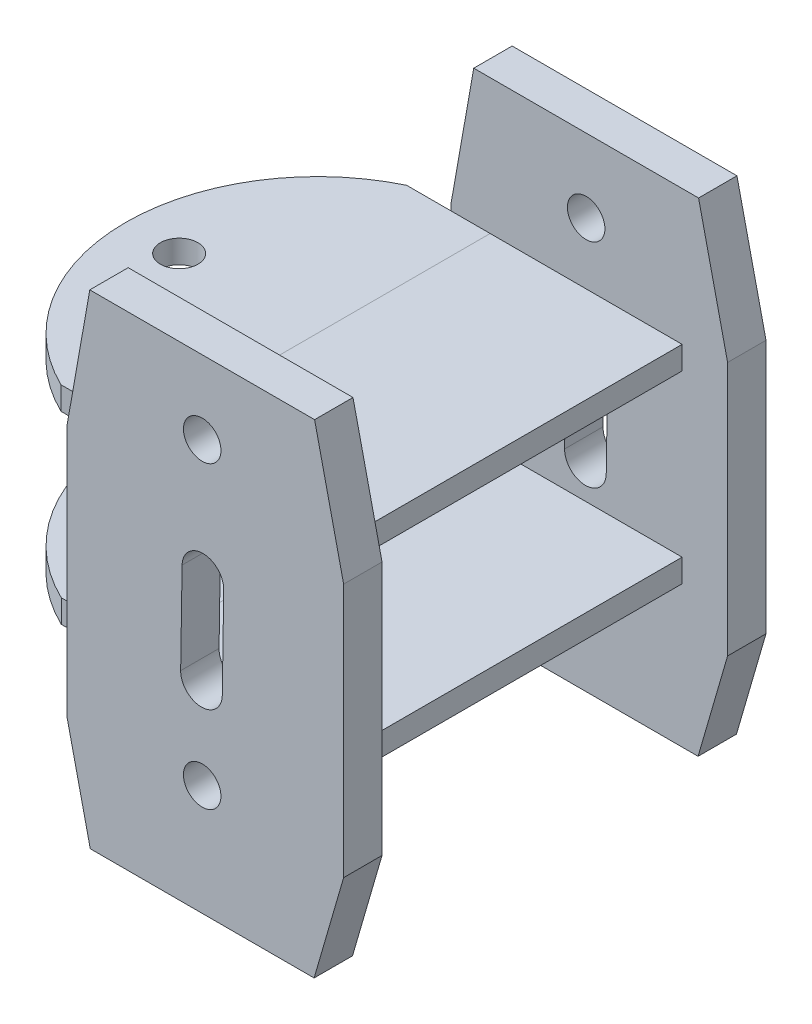
SolidWorks part; units mm, degrees
other "标注1"
sketch "草图13" plane through (-34.4412, -22.5305, 5) normal (-0.9848, -0.1608, 0.0653) x (-0.1462, 0.9714, 0.1873)
material "AISI 1020 钢，冷轧"
ref_plane "前视基准面" through (0, 0, 0) normal (0, 0, 1) x (1, 0, 0)
ref_plane "上视基准面" through (0, 0, 0) normal (0, 1, 0) x (1, 0, 0)
ref_plane "右视基准面" through (0, 0, 0) normal (1, 0, 0) x (0, 0, -1)
sketch "草图1" plane through (0, 0, 0) normal (0, 0, 1) x (1, 0, 0)
  line L0 (17.6966, 40.4695) -> (-11.579, 40.4695)
  line L1 (17.6339, -22.5305) -> (-11.5163, -22.5305)
  line L2 (17.6966, 40.4695) -> (21.478, 23.8119)
  line L3 (21.478, 23.8119) -> (21.478, -9.2898)
  line L4 (21.478, -9.2898) -> (17.6339, -22.5305)
  line L5 (-11.579, 40.4695) -> (-14.522, 23.8119)
  line L6 (-14.522, 23.8119) -> (-14.522, -9.2898)
  line L7 (-14.522, -9.2898) -> (-11.5163, -22.5305)
  line L8 (2.965, 3.401) -> (3.1525, 15.401) construction
  line L9 (-9.4412, 22.8926) -> (15.5588, 22.8926)
  line L12 (-9.4412, 22.8926) -> (-9.4412, 19.8926)
  line L17 (-9.4412, 19.8926) -> (15.5588, 19.8926)
  line L18 (15.5588, 22.8926) -> (15.5588, 19.8926)
  line L19 (-9.4412, 22.8926) -> (15.5588, 19.8926) construction
  line L20 (-9.4412, 19.8926) -> (15.5588, 22.8926) construction
  line L21 (-9.4412, -1.1074) -> (15.5588, -1.1074)
  line L22 (-9.4412, -1.1074) -> (-9.4412, -4.1074)
  line L23 (-9.4412, -4.1074) -> (15.5588, -4.1074)
  line L24 (15.5588, -1.1074) -> (15.5588, -4.1074)
  line L25 (-9.4412, -1.1074) -> (15.5588, -4.1074) construction
  line L26 (-9.4412, -4.1074) -> (15.5588, -1.1074) construction
  line L27 (0.255, 3.4434) -> (0.4425, 15.4434)
  line L28 (5.6751, 3.3587) -> (5.8626, 15.3587)
  circle A0 centre (3.0588, 30.8926) radius 2.44
  circle A1 centre (3.0588, -8.1074) radius 2.44
  arc A8 (0.255, 3.4434) -> (5.6751, 3.3587) centre (2.965, 3.401) ccw
  arc A9 (5.8626, 15.3587) -> (0.4425, 15.4434) centre (3.1525, 15.401) ccw
  point P1 (3.0588, 21.3926)
  point P17 (3.0588, -2.6074)
  point P24 (3.0588, 9.401)
  dimension "D1" = 63
  dimension "D2" = 36
  dimension "D6" = 25
  dimension "D7" = 25
  dimension "D8" = 3
  dimension "D9" = 3
  dimension "D10" = 12
  dimension "D11" = 4
  dimension "D12" = 8
extrude "凸台-拉伸1" add sketch "草图1" along normal blind 5
sketch "草图6" plane through (0, 0, 0) normal (0, 0, -1) x (-1, 0, 0)
  line L42 (9.4412, 22.8926) -> (-15.5588, 22.8926)
  line L43 (9.4412, 19.8926) -> (9.4412, 22.8926)
  line L44 (-15.5588, 19.8926) -> (9.4412, 19.8926)
  line L45 (-15.5588, 22.8926) -> (-15.5588, 19.8926)
  line L46 (9.4412, 22.8926) -> (-15.5588, 22.8926)
  line L47 (9.4412, 19.8926) -> (9.4412, 22.8926)
  line L48 (-15.5588, 19.8926) -> (9.4412, 19.8926)
  line L49 (-15.5588, 22.8926) -> (-15.5588, 19.8926)
  line L54 (-15.5588, -1.1074) -> (-15.5588, -4.1074)
  line L55 (-15.5588, -4.1074) -> (9.4412, -4.1074)
  line L56 (9.4412, -4.1074) -> (9.4412, -1.1074)
  line L57 (9.4412, -1.1074) -> (-15.5588, -1.1074)
  line L58 (-15.5588, -1.1074) -> (-15.5588, -4.1074)
  line L59 (-15.5588, -4.1074) -> (9.4412, -4.1074)
  line L60 (9.4412, -4.1074) -> (9.4412, -1.1074)
  line L61 (9.4412, -1.1074) -> (-15.5588, -1.1074)
  dimension "D1" = 0
  dimension "D2" = 0
extrude "凸台-拉伸5" add sketch "草图6" against normal blind 5 and the other way blind 22.5
mirror "镜向2" about plane through (0, 0, -22.5) normal (0, 0, -1) of bodies 106
sketch "草图7" plane through (-9.4412, 0, 0) normal (-1, 0, 0) x (0, 0, 1)
  line L14 (0, 19.8926) -> (0, 22.8926)
  line L15 (-45, 22.8926) -> (-45, 19.8926)
  line L16 (-45, 19.8926) -> (0, 19.8926)
  line L17 (0, 22.8926) -> (-45, 22.8926)
  line L18 (0, 19.8926) -> (0, 22.8926)
  line L19 (-45, 22.8926) -> (-45, 19.8926)
  line L20 (-45, 19.8926) -> (0, 19.8926)
  line L21 (0, 22.8926) -> (-45, 22.8926)
  dimension "D1" = 0
extrude "凸台-拉伸6" add sketch "草图7" along normal blind 25 separate body
sketch "草图8" plane through (0, 22.8926, 0) normal (0, 1, 0) x (1, 0, 0)
  line L4 (-9.4412, 0) -> (-9.4412, 45)
  line L5 (-9.4412, 45) -> (-34.4412, 45)
  line L6 (-34.4412, 45) -> (-34.4412, 0)
  line L7 (-34.4412, 0) -> (-9.4412, 0)
  line L9 (-9.4412, 45) -> (-34.4412, 45)
  line L10 (-34.4412, 45) -> (-34.4412, 0)
  line L11 (-34.4412, 0) -> (-9.4412, 0)
  line L12 (-9.4412, 0) -> (-9.4412, 45)
  arc A0 (-20.3254, 45) -> (-20.3254, 0) centre (-9.4281, 22.5) ccw
  line M8 (-34.4412, 45) -> (-34.4412, 0)
  line M9 (-34.4412, 0) -> (-9.4412, 0)
  dimension "D2" = 22.5
  dimension "D1" = 0
extrude "切除-拉伸1" cut sketch "草图8" against normal blind 3 contours A0 L9 M8 M9
sketch "草图9" plane through (-9.4412, 0, 0) normal (-1, 0, 0) x (0, 0, 1)
  line L4 (0, -4.1074) -> (0, -1.1074)
  line L5 (0, -1.1074) -> (-45, -1.1074)
  line L6 (-45, -1.1074) -> (-45, -4.1074)
  line L7 (-45, -4.1074) -> (0, -4.1074)
  line L8 (0, -4.1074) -> (0, -1.1074)
  line L9 (0, -1.1074) -> (-45, -1.1074)
  line L10 (-45, -1.1074) -> (-45, -4.1074)
  line L11 (-45, -4.1074) -> (0, -4.1074)
  dimension "D1" = 0
extrude "凸台-拉伸7" add sketch "草图9" along normal blind 25 separate body
sketch "草图10" plane through (0, -1.1074, 0) normal (0, 1, 0) x (1, 0, 0)
  line L4 (-9.4412, 0) -> (-9.4412, 45)
  line L5 (-9.4412, 45) -> (-34.4412, 45)
  line L6 (-34.4412, 45) -> (-34.4412, 0)
  line L7 (-34.4412, 0) -> (-9.4412, 0)
  line L8 (-9.4412, 0) -> (-9.4412, 45)
  line L9 (-9.4412, 45) -> (-34.4412, 45)
  line L10 (-34.4412, 45) -> (-34.4412, 0)
  line L11 (-34.4412, 0) -> (-9.4412, 0)
  arc A0 (-20.2893, 45) -> (-20.2893, 0) centre (-9.479, 22.5) ccw
  line M7 (-34.4412, 45) -> (-34.4412, 0)
  line M8 (-34.4412, 0) -> (-9.4412, 0)
  dimension "D2" = 22.5
  dimension "D1" = 0
extrude "切除-拉伸2" cut sketch "草图10" against normal blind 3 contours A0 L9 M7 | A0 L10 M8
sketch "草图11" plane through (0, 22.8926, 0) normal (0, 1, 0) x (1, 0, 0)
  line L3 (-20.3254, 0) -> (-9.4412, 0)
  line L4 (-9.4412, 0) -> (-9.4412, 45)
  line L5 (-9.4412, 45) -> (-20.3254, 45)
  line L6 (-20.3254, 0) -> (-9.4412, 0)
  line L7 (-9.4412, 0) -> (-9.4412, 45)
  line L8 (-9.4412, 45) -> (-20.3254, 45)
  circle A0 centre (-27.4412, 22.5) radius 2.44
  arc A1 (-20.3254, 45) -> (-20.3254, 0) centre (-9.4281, 22.5) ccw
  arc A2 (-20.3254, 45) -> (-20.3254, 0) centre (-9.4281, 22.5) ccw
  dimension "D2" = 18
  dimension "D1" = 0
extrude "切除-拉伸4" cut sketch "草图11" against normal blind 27 contours A0
sketch "草图3" plane through (0, 0, 5) normal (0, 0, 1) x (1, 0, 0)
  line L28 (5.6751, 3.3587) -> (5.8626, 15.3587)
  line L29 (0.4425, 15.4434) -> (0.255, 3.4434)
  line L30 (5.6751, 3.3587) -> (5.8626, 15.3587)
  line L31 (0.4425, 15.4434) -> (0.255, 3.4434)
  arc A28 (5.8626, 15.3587) -> (0.4425, 15.4434) centre (3.1525, 15.401) ccw
  arc A29 (0.255, 3.4434) -> (5.6751, 3.3587) centre (2.965, 3.401) ccw
  arc A30 (5.8626, 15.3587) -> (0.4425, 15.4434) centre (3.1525, 15.401) ccw
  arc A31 (0.255, 3.4434) -> (5.6751, 3.3587) centre (2.965, 3.401) ccw
  dimension "D1" = 0
